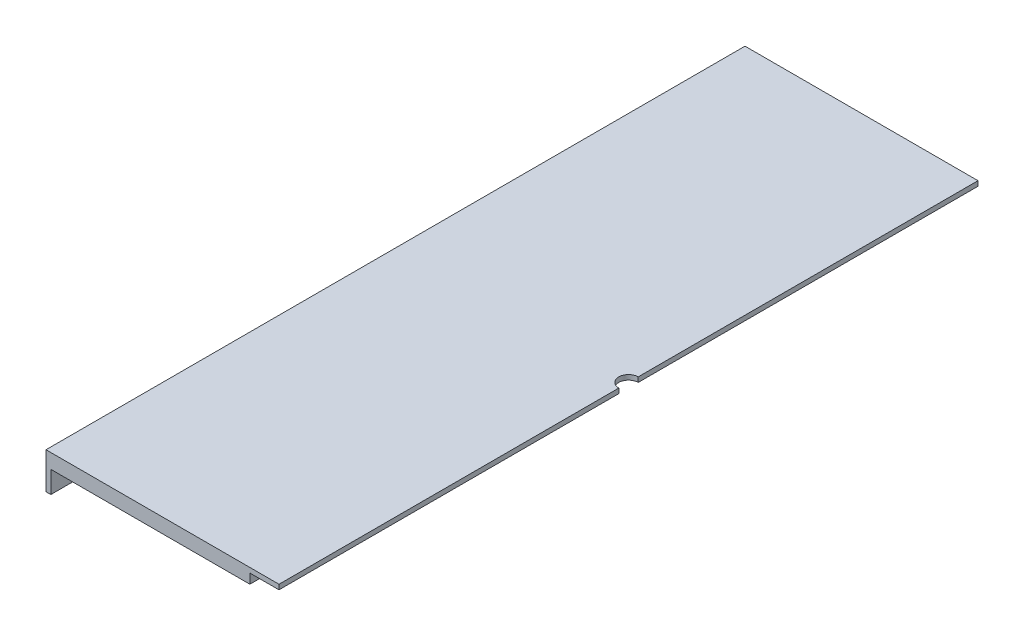
SolidWorks part; units mm, degrees
ref_plane "Front Plane" through (0, 0, 0) normal (0, 0, 1) x (1, 0, 0)
ref_plane "Top Plane" through (0, 0, 0) normal (0, 1, 0) x (1, 0, 0)
ref_plane "Right Plane" through (0, 0, 0) normal (1, 0, 0) x (0, 0, -1)
sketch "Sketch1" plane through (0, 0, 0) normal (0, 1, 0) x (1, 0, 0)
  line L1 (0, 0) -> (152.4, 0)
  line L2 (0, 0) -> (0, 457.2)
  line L3 (0, 457.2) -> (152.4, 457.2)
  line L4 (152.4, 0) -> (152.4, 457.2)
  dimension "D1" = 152.4
  dimension "D2" = 457.2
extrude "Boss-Extrude1" add sketch "Sketch1" along normal blind 3.175
sketch "Sketch2" plane through (0, 3.175, 0) normal (0, 1, 0) x (1, 0, 0)
  line L5 (0, 0) -> (152.4, 0) construction
  line L6 (76.2, 0) -> (76.2, 457.2) construction
  line L7 (152.4, 457.2) -> (0, 457.2) construction
  line L8 (3.175, 457.2) -> (3.175, 0)
  line L9 (0, 0) -> (3.175, 0)
  line L10 (0, 457.2) -> (0, 0)
  line L11 (0, 457.2) -> (3.175, 457.2)
extrude "Boss-Extrude2" add sketch "Sketch2" against normal blind 23.8125
sketch "Sketch3" plane through (0, 0, 0) normal (0, -1, 0) x (1, 0, 0)
  line L0 (0, -457.2) -> (0, 0) construction
  line L1 (0, -106.3625) -> (133.35, -106.3625)
  line L2 (0, -106.3625) -> (0, -109.5375)
  line L3 (0, -109.5375) -> (133.35, -109.5375)
  line L4 (133.35, -106.3625) -> (133.35, -109.5375)
  line L7 (133.35, -227.0125) -> (0, -227.0125)
  line L8 (133.35, -227.0125) -> (133.35, -230.1875)
  line L9 (133.35, -230.1875) -> (0, -230.1875)
  line L10 (0, -227.0125) -> (0, -230.1875)
  line L11 (133.35, -347.6625) -> (0, -347.6625)
  line L12 (133.35, -347.6625) -> (133.35, -350.8375)
  line L13 (133.35, -350.8375) -> (0, -350.8375)
  line L14 (0, -347.6625) -> (0, -350.8375)
  line L16 (3.175, 0) -> (152.4, 0) construction
  line L17 (0, 0) -> (133.35, 0)
  line L18 (0, 0) -> (0, -3.175)
  line L19 (0, -3.175) -> (133.35, -3.175)
  line L20 (133.35, 0) -> (133.35, -3.175)
  line L21 (133.35, -454.025) -> (0, -454.025)
  line L22 (133.35, -454.025) -> (133.35, -457.2)
  line L23 (133.35, -457.2) -> (0, -457.2)
  line L24 (0, -454.025) -> (0, -457.2)
  line L25 (152.4, -457.2) -> (3.175, -457.2) construction
  dimension "D1" = 3.175
  dimension "D2" = 3.175
  dimension "D3" = 3.175
  dimension "D4" = 3.175
  dimension "D5" = 117.475
  dimension "D6" = 117.475
  dimension "D7" = 3.175
  dimension "D8" = 103.1875
  dimension "D9" = 133.35
  dimension "D10" = 133.35
  dimension "D11" = 133.35
  dimension "D12" = 133.35
  dimension "D13" = 133.35
extrude "Boss-Extrude3" add sketch "Sketch3" along normal blind 6.35
sketch "Sketch9" plane through (0, 0, 0) normal (0, -1, 0) x (1, 0, 0)
  line L0 (3.175, -457.2) -> (133.35, -457.2) construction
  line L1 (133.35, 0) -> (130.175, 0)
  line L2 (133.35, 0) -> (133.35, -457.2)
  line L3 (133.35, -457.2) -> (130.175, -457.2)
  line L4 (130.175, 0) -> (130.175, -457.2)
  dimension "D1" = 3.175
extrude "Boss-Extrude4" add sketch "Sketch9" along normal up to surface (6.35 mm away) up to face at (68.2625, -6.35, -349.25)
sketch "Sketch11" plane through (0, 3.175, 0) normal (0, 1, 0) x (1, 0, 0)
  line L0 (152.4, 457.2) -> (152.4, 228.6) construction
  line L1 (152.4, 0) -> (152.4, 457.2) construction
  circle A0 centre (152.4, 228.6) radius 6.35
extrude "Cut-Extrude1" cut sketch "Sketch11" against normal through all
